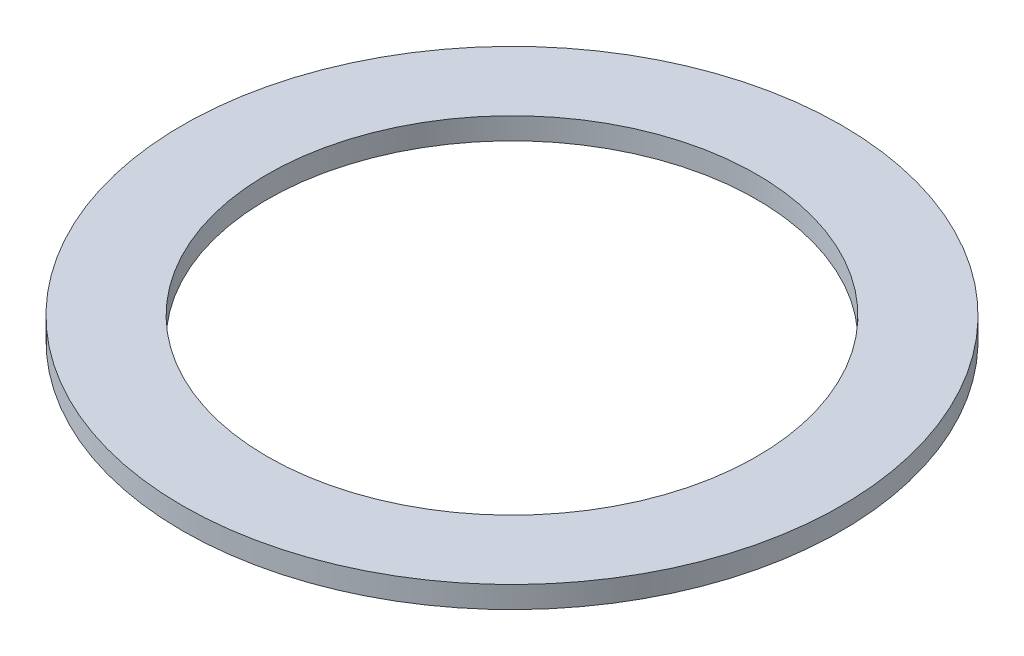
SolidWorks part; units mm, degrees
ref_plane "前视基准面" through (0, 0, 0) normal (0, 0, 1) x (1, 0, 0)
ref_plane "上视基准面" through (0, 0, 0) normal (0, 1, 0) x (1, 0, 0)
ref_plane "右视基准面" through (0, 0, 0) normal (1, 0, 0) x (0, 0, -1)
other "Configuration Table"
sketch "草图1" plane through (0, 0, 0) normal (0, 1, 0) x (1, 0, 0)
  circle A0 centre (0, 0) radius 60.625
  circle A1 centre (0, 0) radius 45
  dimension "D1" = 121.25
  dimension "D2" = 90
extrude "凸台-拉伸1" add sketch "草图1" along normal blind 4
